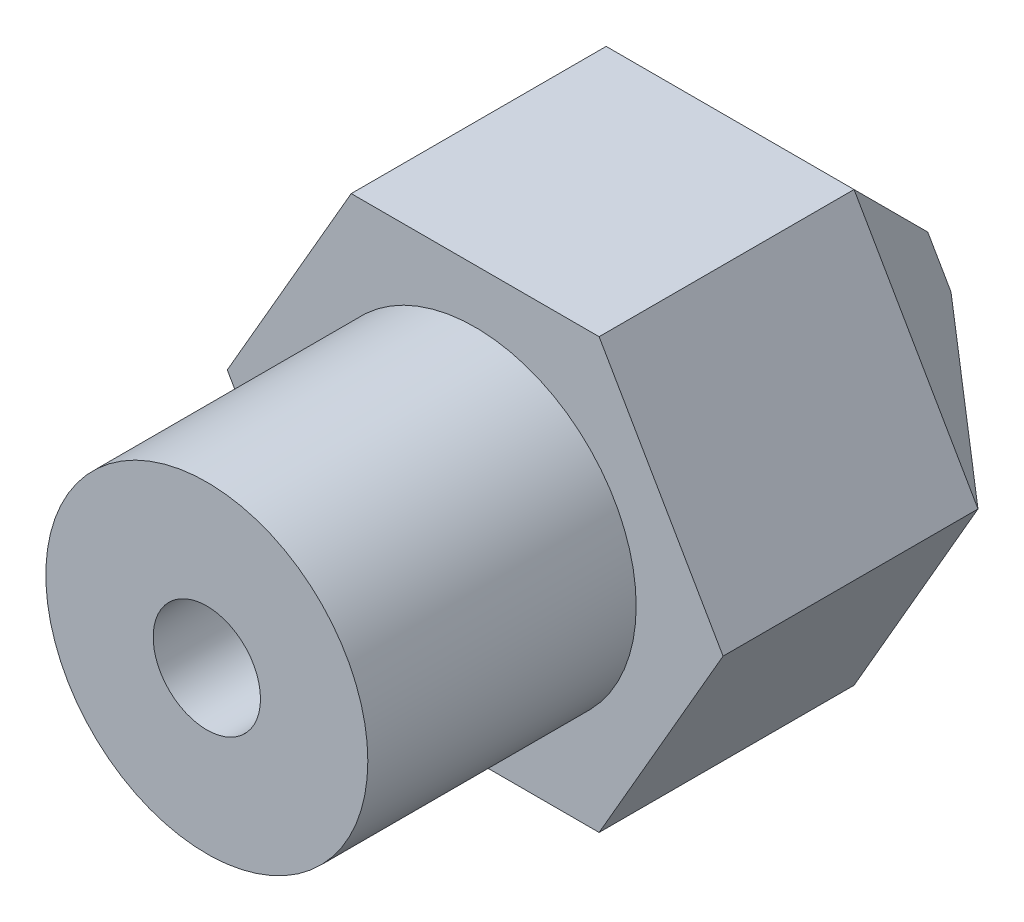
SolidWorks part; units mm, degrees
ref_plane "Plan de face" through (0, 0, 0) normal (0, 0, 1) x (1, 0, 0)
ref_plane "Plan de dessus" through (0, 0, 0) normal (0, 1, 0) x (1, 0, 0)
ref_plane "Plan de droite" through (0, 0, 0) normal (1, 0, 0) x (0, 0, -1)
sketch "Esquisse1" plane through (0, 0, 0) normal (0, 0, 1) x (1, 0, 0)
  line L1 (4.6188, 0) -> (2.3094, 4)
  line L2 (2.3094, 4) -> (-2.3094, 4)
  line L3 (-2.3094, 4) -> (-4.6188, 0)
  line L4 (-4.6188, 0) -> (-2.3094, -4)
  line L5 (-2.3094, -4) -> (2.3094, -4)
  line L6 (2.3094, -4) -> (4.6188, 0)
  circle A0 centre (0, 0) radius 4 construction
  dimension "D1" = 8
extrude "Boss.-Extru.1" add sketch "Esquisse1" along normal blind 13
sketch "Esquisse2" plane through (0, 0, 13) normal (0, 0, 1) x (1, 0, 0)
  line L1 (-10.6589, 5.9418) -> (8.2153, 5.9418)
  line L2 (-10.6589, 5.9418) -> (-10.6589, -6.0867)
  line L3 (-10.6589, -6.0867) -> (8.2153, -6.0867)
  line L4 (8.2153, 5.9418) -> (8.2153, -6.0867)
  circle A0 centre (0, 0) radius 3
  dimension "D1" = 6
extrude "Enlèv. mat.-Extru.1" cut sketch "Esquisse2" against normal blind 5
cosmetic thread "Représentation de filetage1" parameters "D1"=5, "D2"=4.891
chamfer "Chanfrein1" distance 3.25 angle 45 6 edges at (3.4641, 2, 0) (0, 4, 0) (-3.4641, 2, 0) (-3.4641, -2, 0) (0, -4, 0) (3.4641, -2, 0)
hole_wizard "Diamètre du perçage Ø1.5 (1.5)1" positions "Esquisse4" profile "Esquisse3" hole size "Ø1.5" standard "ISO"
sketch "Esquisse4" plane through (0, 0, 13) normal (0, 0, 1) x (1, 0, 0)
  point P0 (0, 0)
sketch "Esquisse3" plane through (0, 0, 13) normal (1, 0, 0) x (0, -1, 0)
  line L0 (0, 0) -> (0, 12.5506)
  line L1 (0, 12.5506) -> (0.75, 12.1)
  line L2 (0.75, 12.1) -> (0.75, 0)
  line L5 (0.75, 0) -> (0, 0)
  line L10 (0, 12.5506) -> (-0.75, 12.1) construction
  line L11 (0, -6.35) -> (0, 107.95) construction
  dimension "Diamètre du perçage" = 1.5
  dimension "Profondeur du perçage" = 12.1
  dimension "Angle de pointe" = 118
hole_wizard "Diamètre du perçage Ø2.0 (2)1" positions "Esquisse6" profile "Esquisse5" hole size "Ø2.0" standard "ISO"
sketch "Esquisse6" plane through (0, 0, 13) normal (0, 0, 1) x (1, 0, 0)
  point P0 (0, 0)
sketch "Esquisse5" plane through (0, 0, 13) normal (1, 0, 0) x (0, -1, 0)
  line L0 (0, 0) -> (0, 11.2009)
  line L1 (0, 11.2009) -> (1, 10.6)
  line L2 (1, 10.6) -> (1, 0)
  line L5 (1, 0) -> (0, 0)
  line L10 (0, 11.2009) -> (-1, 10.6) construction
  line L11 (0, -6.35) -> (0, 107.95) construction
  dimension "Diamètre du perçage" = 2
  dimension "Profondeur du perçage" = 10.6
  dimension "Angle de pointe" = 118
hole_wizard "Diamètre du perçage Ø0.4 (0.4)1" positions "Esquisse8" profile "Esquisse7" hole size "Ø0.4" standard "ISO"
sketch "Esquisse8" plane through (0, 0, 0) normal (0, 0, -1) x (-1, 0, 0)
  point P0 (0, 0)
sketch "Esquisse7" plane through (0, 0, 0) normal (1, 0, 0) x (0, 1, 0)
  line L0 (0, 0) -> (0, 1.1202)
  line L1 (0, 1.1202) -> (0.2, 1)
  line L2 (0.2, 1) -> (0.2, 0)
  line L5 (0.2, 0) -> (0, 0)
  line L10 (0, 1.1202) -> (-0.2, 1) construction
  line L11 (0, -6.35) -> (0, 107.95) construction
  dimension "Diamètre du perçage" = 0.4
  dimension "Profondeur du perçage" = 1
  dimension "Angle de pointe" = 118
